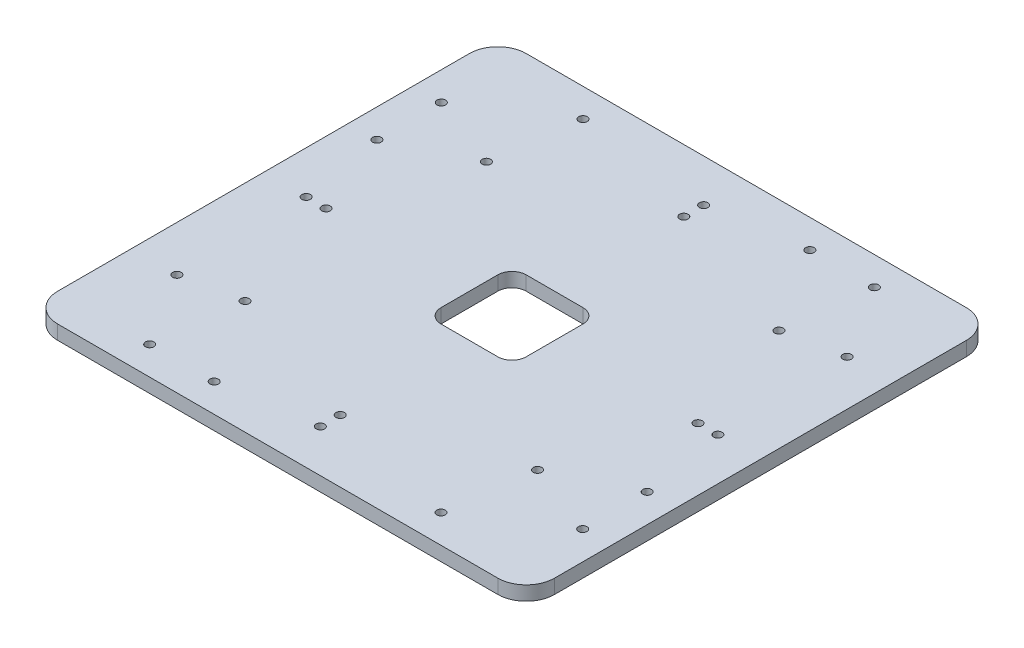
SolidWorks part; units mm, degrees
material "Acrílico (médio-alto impacto)"
ref_plane "Plano frontal" through (0, 0, 0) normal (0, 0, 1) x (1, 0, 0)
ref_plane "Plano superior" through (0, 0, 0) normal (0, 1, 0) x (1, 0, 0)
ref_plane "Plano direito" through (0, 0, 0) normal (1, 0, 0) x (0, 0, -1)
sketch "Esboço1" plane through (0, 0, 0) normal (0, 1, 0) x (1, 0, 0)
  line L1 (-25.613, 137.6647) -> (129.387, 137.6647)
  line L2 (-35.613, 127.6647) -> (-35.613, -17.3353)
  line L3 (-25.613, -27.3353) -> (129.387, -27.3353)
  line L4 (139.387, 127.6647) -> (139.387, -17.3353)
  arc A0 (129.387, 137.6647) -> (139.387, 127.6647) centre (129.387, 127.6647) cw
  arc A1 (129.387, -27.3353) -> (139.387, -17.3353) centre (129.387, -17.3353) ccw
  arc A2 (-35.613, -17.3353) -> (-25.613, -27.3353) centre (-25.613, -17.3353) ccw
  arc A3 (-25.613, 137.6647) -> (-35.613, 127.6647) centre (-25.613, 127.6647) ccw
  dimension "D1" = 10
  dimension "D5" = 10
  dimension "D6" = 10
  dimension "D7" = 10
  dimension "D2" = 155
  dimension "D3" = 145
  dimension "D4" = 155
  dimension "D8" = 145
extrude "Ressalto-extrusão1" add sketch "Esboço1" along normal blind 5
sketch "Esboço2" plane through (0, 5, 0) normal (0, 1, 0) x (1, 0, 0)
  line L0 (-35.613, 127.6647) -> (-35.613, -17.3353) construction
  line L3 (-25.613, -27.3353) -> (129.387, -27.3353) construction
  circle A0 centre (0.387, 97.6647) radius 1.5
  circle A1 centre (103.387, 97.6647) radius 1.5
  circle A2 centre (0.387, 12.6647) radius 1.5
  circle A3 centre (103.387, 12.6647) radius 1.5
  dimension "D1" = 103
  dimension "D2" = 103
  dimension "D3" = 85
  dimension "D4" = 85
  dimension "D5" = 3
  dimension "D6" = 3
  dimension "D7" = 3
  dimension "D8" = 3
  dimension "D9" = 36
  dimension "D10" = 40
extrude "Corte-extrusão1" cut sketch "Esboço2" against normal blind 10
sketch "Esboço3" plane through (0, 5, 0) normal (0, 1, 0) x (1, 0, 0)
  line L0 (-35.613, 127.6647) -> (-35.613, -17.3353) construction
  line L2 (-25.613, -27.3353) -> (129.387, -27.3353) construction
  line L3 (129.387, 137.6647) -> (-25.613, 137.6647) construction
  line L4 (51.887, 137.6647) -> (51.887, -27.3353) construction
  line L5 (-35.613, 55.1647) -> (139.387, 55.1647) construction
  line L6 (139.387, -17.3353) -> (139.387, 127.6647) construction
  circle A0 centre (51.887, -5.3353) radius 1.5
  circle A1 centre (51.887, -12.3353) radius 1.5
  circle A2 centre (-20.613, 55.1647) radius 1.5
  circle A3 centre (-13.613, 55.1647) radius 1.5
  circle A4 centre (51.887, 122.6647) radius 1.5
  circle A5 centre (51.887, 115.6647) radius 1.5
  circle A6 centre (124.387, 55.1647) radius 1.5
  circle A7 centre (117.387, 55.1647) radius 1.5
  point P8 (51.887, -27.3353)
  dimension "D1" = 7
  dimension "D2" = 3
  dimension "D3" = 3
  dimension "D4" = 87.5
  dimension "D5" = 15
  dimension "D6" = 3
  dimension "D7" = 3
  dimension "D8" = 7
  dimension "D9" = 82.5
  dimension "D10" = 15
extrude "Corte-extrusão2" cut sketch "Esboço3" against normal blind 15
sketch "Esboço4" plane through (0, 5, 0) normal (0, 1, 0) x (1, 0, 0)
  line L0 (51.887, -27.3353) -> (51.887, 137.6647) construction
  line L1 (-25.613, -27.3353) -> (129.387, -27.3353) construction
  line L2 (129.387, 137.6647) -> (-25.613, 137.6647) construction
  line L5 (-35.613, 127.6647) -> (-35.613, -17.3353) construction
  line L6 (139.387, 55.1647) -> (-35.613, 55.1647) construction
  line L7 (139.387, -17.3353) -> (139.387, 127.6647) construction
  circle A0 centre (-3.213, -17.3353) radius 1.5
  circle A1 centre (19.487, -17.3353) radius 1.5
  circle A2 centre (-25.613, 107.7647) radius 1.5
  circle A3 centre (-25.613, 85.0647) radius 1.5
  circle A4 centre (106.987, 127.6647) radius 1.5
  circle A5 centre (84.287, 127.6647) radius 1.5
  circle A6 centre (129.387, 2.5647) radius 1.5
  circle A7 centre (129.387, 25.2647) radius 1.5
  dimension "D1" = 22.7
  dimension "D2" = 3
  dimension "D3" = 3
  dimension "D4" = 32.4
  dimension "D5" = 10
  dimension "D6" = 10
  dimension "D7" = 32.4
  dimension "D8" = 22.7
  dimension "D9" = 3
  dimension "D10" = 3
  dimension "D11" = 10
  dimension "D12" = 29.9
  dimension "D13" = 29.9
  dimension "D14" = 22.7
  dimension "D15" = 3
  dimension "D16" = 3
  dimension "D17" = 32.4
  dimension "D18" = 10
  dimension "D19" = 22.7
  dimension "D20" = 3
  dimension "D21" = 3
  dimension "D22" = 29.9
  dimension "D23" = 29.9
  dimension "D24" = 10
  dimension "D25" = 10
extrude "Corte-extrusão3" cut sketch "Esboço4" against normal blind 10
sketch "Esboço5" plane through (0, 5, 0) normal (0, 1, 0) x (1, 0, 0)
  line L0 (-25.613, -27.3353) -> (129.387, -27.3353) construction
  line L1 (41.887, 40.1647) -> (61.887, 40.1647)
  line L2 (36.887, 45.1647) -> (36.887, 65.1647)
  line L3 (41.887, 70.1647) -> (61.887, 70.1647)
  line L4 (66.887, 45.1647) -> (66.887, 65.1647)
  line L6 (129.387, 137.6647) -> (-25.613, 137.6647) construction
  line L9 (-35.613, 127.6647) -> (-35.613, -17.3353) construction
  line L10 (139.387, -17.3353) -> (139.387, 127.6647) construction
  arc A0 (36.887, 65.1647) -> (41.887, 70.1647) centre (41.887, 65.1647) cw
  arc A1 (61.887, 70.1647) -> (66.887, 65.1647) centre (61.887, 65.1647) cw
  arc A2 (61.887, 40.1647) -> (66.887, 45.1647) centre (61.887, 45.1647) ccw
  arc A3 (41.887, 40.1647) -> (36.887, 45.1647) centre (41.887, 45.1647) cw
  dimension "D1" = 5
  dimension "D2" = 67.5
  dimension "D3" = 67.5
  dimension "D4" = 72.5
  dimension "D5" = 72.5
extrude "Corte-extrusão4" cut sketch "Esboço5" against normal blind 10
sketch "Esboço6" plane through (0, 5, 0) normal (0, 1, 0) x (1, 0, 0)
  line L0 (-35.613, 127.6647) -> (-35.613, -17.3353) construction
  line L1 (-25.613, -27.3353) -> (129.387, -27.3353) construction
  line L2 (139.387, -17.3353) -> (139.387, 127.6647) construction
  line L3 (129.387, 137.6647) -> (-25.613, 137.6647) construction
  circle A0 centre (-19.613, 8.6647) radius 1.5
  circle A1 centre (123.387, 101.6647) radius 1.5
  circle A2 centre (4.387, 127.6647) radius 1.5
  circle A3 centre (99.387, -17.3353) radius 1.5
  dimension "D1" = 16
  dimension "D2" = 36
  dimension "D3" = 16
  dimension "D4" = 36
  dimension "D5" = 10
  dimension "D6" = 40
  dimension "D7" = 10
  dimension "D8" = 40
  dimension "D9" = 3
  dimension "D10" = 3
  dimension "D11" = 3
  dimension "D12" = 3
extrude "Corte-extrusão5" cut sketch "Esboço6" against normal blind 10
